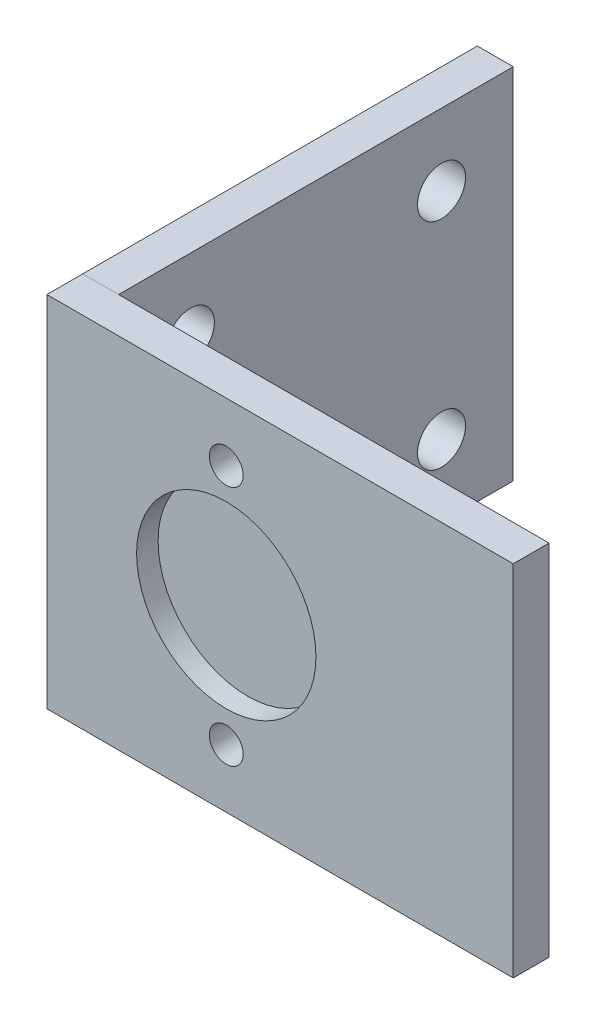
SolidWorks part; units mm, degrees
ref_plane "Front Plane" through (0, 0, 0) normal (0, 0, 1) x (1, 0, 0)
ref_plane "Top Plane" through (0, 0, 0) normal (0, 1, 0) x (1, 0, 0)
ref_plane "Right Plane" through (0, 0, 0) normal (1, 0, 0) x (0, 0, -1)
sketch "Sketch1" plane through (0, 0, 0) normal (1, 0, 0) x (0, 0, -1)
  line L0 (-31.8768, 23.0863) -> (-31.8768, -16.3439) construction
  line L2 (-44.5768, 4.0363) -> (-5.3691, 4.0363) construction
  line L4 (-45.8468, 16.7363) -> (-17.9068, 16.7363)
  line L5 (-40.7668, -3.5837) -> (-22.9868, -3.5837) construction
  line L6 (-40.7668, -3.5837) -> (-40.7668, 11.6563) construction
  line L7 (-40.7668, 11.6563) -> (-22.9868, 11.6563) construction
  line L8 (-22.9868, -3.5837) -> (-22.9868, 11.6563) construction
  line L9 (-40.7668, -3.5837) -> (-22.9868, 11.6563) construction
  line L10 (-40.7668, 11.6563) -> (-22.9868, -3.5837) construction
  line L11 (-17.9068, -8.6637) -> (-17.9068, 16.7363)
  line L12 (-45.8468, -8.6637) -> (-17.9068, -8.6637)
  line L13 (-45.8468, -8.6637) -> (-45.8468, 16.7363)
  point P1 (0, 0)
  point P16 (0, 0)
  point P17 (-31.8768, 4.0363)
  point P18 (0, 0)
  point P25 (0, 0)
  point P30 (0, 0)
  dimension "D1" = 5.08
extrude "side connecting to grip" add sketch "Sketch1" along normal blind 2.54 separate body
hole_wizard "M3 Clearance Hole1" positions "Sketch4" profile "Sketch5" hole size "M3" standard "ANSI Metric" end condition through all
sketch "Sketch4" plane through (2.54, 0, 0) normal (1, 0, 0) x (0, 0, -1)
  point P0 (-40.7668, 11.6563)
  point P3 (-22.9868, 11.6563)
  point P6 (-22.9868, -3.5837)
  point P9 (-40.7668, -3.5837)
sketch "Sketch5" plane through (2.54, 11.6563, 40.7668) normal (0, 1, 0) x (0, 0, -1)
  line L0 (0, 0) -> (0, 2.54)
  line L1 (0, 2.54) -> (1.7, 2.54)
  line L2 (1.7, 2.54) -> (1.7, 0)
  line L5 (1.7, 0) -> (0, 0)
  line L11 (0, -6.35) -> (0, 107.95) construction
  dimension "Thru Hole Dia." = 3.4
  dimension "Thru Hole Depth" = 2.54
sketch "Sketch6" plane through (2.54, 0, 0) normal (1, 0, 0) x (0, 0, -1)
  line L42 (-45.8468, 16.7363) -> (-48.3868, 16.7363)
  line L43 (-48.3868, 16.7363) -> (-48.3868, -8.6637)
  line L44 (-48.3868, -8.6637) -> (-45.8468, -8.6637)
  line L45 (-45.8468, -8.6637) -> (-45.8468, 16.7363) construction
  line L46 (-45.8468, 16.7363) -> (-45.8468, -8.6637)
  dimension "D1" = 2.54
extrude "side connecting to servo" add sketch "Sketch6" along normal blind 30.48 and the other way blind 2.54 separate body
sketch "servo holes" plane through (0, 0, 48.3868) normal (0, 0, 1) x (1, 0, 0)
  line L0 (0, 4.0363) -> (36.6866, 4.0363) construction
  line L1 (0, -8.6637) -> (0, 16.7363) construction
  circle A0 centre (12.7, 4.0363) radius 8.55 construction
  point P5 (12.7, -4.5137)
  point P8 (12.7, 12.5863)
  dimension "D1" = 17.1
  dimension "D2" = 12.7
hole_wizard "cutout servo holes" positions "Sketch8" profile "Sketch9" hole size "M2" standard "ANSI Metric" end condition through all
sketch "Sketch8" plane through (0, 0, 48.3868) normal (0, 0, 1) x (1, 0, 0)
  point P0 (12.7, 12.5863)
  point P3 (12.7, -4.5137)
sketch "Sketch9" plane through (12.7, 12.5863, 48.3868) normal (1, 0, 0) x (0, -1, 0)
  line L0 (0, 0) -> (0, 30.48)
  line L1 (0, 30.48) -> (1.2, 30.48)
  line L2 (1.2, 30.48) -> (1.2, 0)
  line L5 (1.2, 0) -> (0, 0)
  line L11 (0, -6.35) -> (0, 107.95) construction
  dimension "Thru Hole Dia." = 2.4
  dimension "Thru Hole Depth" = 30.48
sketch "Sketch10" plane through (0, 0, 48.3868) normal (0, 0, 1) x (1, 0, 0)
  circle A0 centre (12.7, 4.0363) radius 6.35
  dimension "D1" = 12.7
extrude "Cut-Extrude1" cut sketch "Sketch10" against normal blind 1.524
